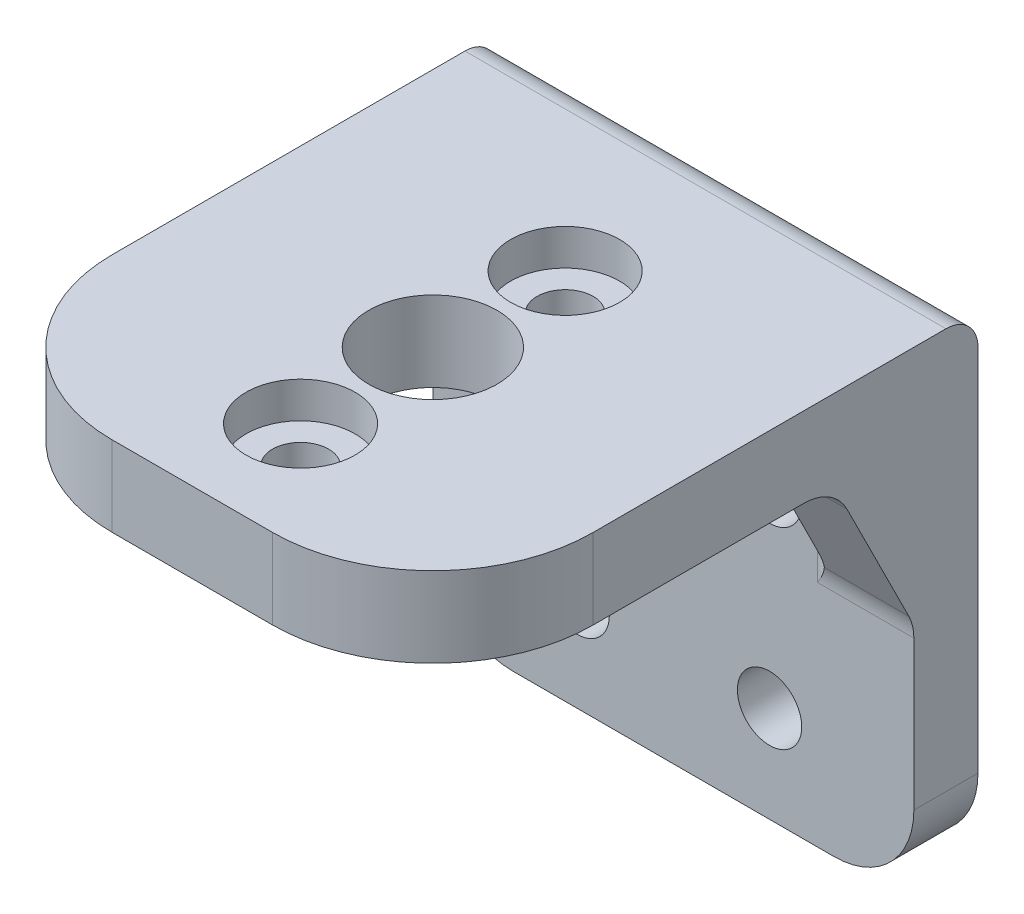
SolidWorks part; units mm, degrees
ref_plane "Alzado" through (0, 0, 0) normal (0, 0, 1) x (1, 0, 0)
ref_plane "Planta" through (0, 0, 0) normal (0, 1, 0) x (1, 0, 0)
ref_plane "Vista lateral" through (0, 0, 0) normal (1, 0, 0) x (0, 0, -1)
sketch "Croquis1" plane through (0, 0, 0) normal (0, 0, 1) x (1, 0, 0)
  line L0 (0, 21.15) -> (0, 30)
  line L1 (0, 0) -> (30, 0)
  line L2 (0, 0) -> (0, 14.85)
  line L3 (0, 30) -> (30, 30)
  line L4 (30, 0) -> (30, 14.85)
  line L5 (30, 21.15) -> (30, 30)
  line L6 (0, 21.15) -> (0, 14.85)
  line L7 (30, 21.15) -> (30, 14.85)
  circle A0 centre (9, 18) radius 2.0051
  circle A1 centre (21, 18) radius 2.0051
  circle A2 centre (21, 6) radius 2.0051
  circle A3 centre (9, 6) radius 2.0051
  dimension "D1" = 30
  dimension "D2" = 30
  dimension "D3" = 12
  dimension "D4" = 9
  dimension "D5" = 2
  dimension "D6" = 2
extrude "Saliente-Extruir1" add sketch "Croquis1" along normal blind 4
sketch "Croquis2" plane through (0, 0, 4) normal (0, 0, 1) x (1, 0, 0)
  line L0 (30, 0) -> (30, 30) construction
  line L1 (0, 30) -> (30, 30)
  line L2 (0, 30) -> (0, 25)
  line L3 (0, 25) -> (30, 25)
  line L4 (30, 30) -> (30, 25)
  dimension "D1" = 5
extrude "Saliente-Extruir2" add sketch "Croquis2" along normal blind 30
sketch "Croquis3" plane through (0, 25, 0) normal (0, -1, 0) x (1, 0, 0)
  line L0 (15, 4) -> (15, 34) construction
  line L1 (0, 4) -> (30, 4) construction
  line L2 (0, 34) -> (30, 34) construction
  line L3 (15, 19) -> (0, 19) construction
  line L4 (0, 34) -> (0, 4) construction
  line L5 (0, 0) -> (30, 0) construction
  line L6 (0, 4) -> (30, 4) construction
  line L7 (0, 34) -> (30, 34) construction
  circle A0 centre (15, 27.25) radius 1.75
  circle A1 centre (15, 10.75) radius 1.75
  circle A2 centre (15, 19) radius 4
  dimension "D3" = 8
  dimension "D4" = 3.5
  dimension "D5" = 3.5
  dimension "D1" = 16.5
extrude "Cortar-Extruir1" cut sketch "Croquis3" against normal through all
fillet "Redondeo1" radius 10 2 edges at (30, 27.5, 34) (0, 27.5, 34)
fillet "Redondeo2" radius 5 2 edges at (0, 0, 2) (30, 0, 2)
fillet "Redondeo4" radius 2 1 edges at (15, 30, 0)
sketch "Croquis4" plane through (0, 30, 0) normal (0, 1, 0) x (1, 0, 0)
  circle A0 centre (15, -10.75) radius 3.4
  circle A1 centre (15, -27.25) radius 3.4
  dimension "D1" = 6.8
  dimension "D2" = 6.8
extrude "Cortar-Extruir2" cut sketch "Croquis4" against normal blind 2.25
sketch "Croquis7" plane through (30, 0, 0) normal (1, 0, 0) x (0, 0, -1)
  line L0 (-9, 25) -> (-4, 15)
  line L1 (-4, 5) -> (-4, 25) construction
rib "Nervio12" sketch "Croquis7" sketch "Croquis7" thickness 5 extrusion direction parallel to sketch draft on no parameters "D1"=5
sketch "Croquis8" plane through (0, 0, 0) normal (-1, 0, 0) x (0, 0, 1)
  line L0 (4, 15) -> (9, 25)
rib "Nervio13" sketch "Croquis8" sketch "Croquis8" thickness 5 extrusion direction parallel to sketch draft on no parameters "D1"=5
fillet "Redondeo6" radius 3 4 edges at (27.5, 15, 4) (2.5, 15, 4) (27.5, 25, 9) (2.5, 25, 9)
fillet "Redondeo7" radius 2 1 edges at (15, 25, 4)
fillet "Redondeo8" radius 1 6 edges at (5, 25, 8.4271) (5, 24.4142, 4.5858) (5, 18.6459, 4) (25, 25, 8.4271) (25, 24.4142, 4.5858) (25, 18.6459, 4)
